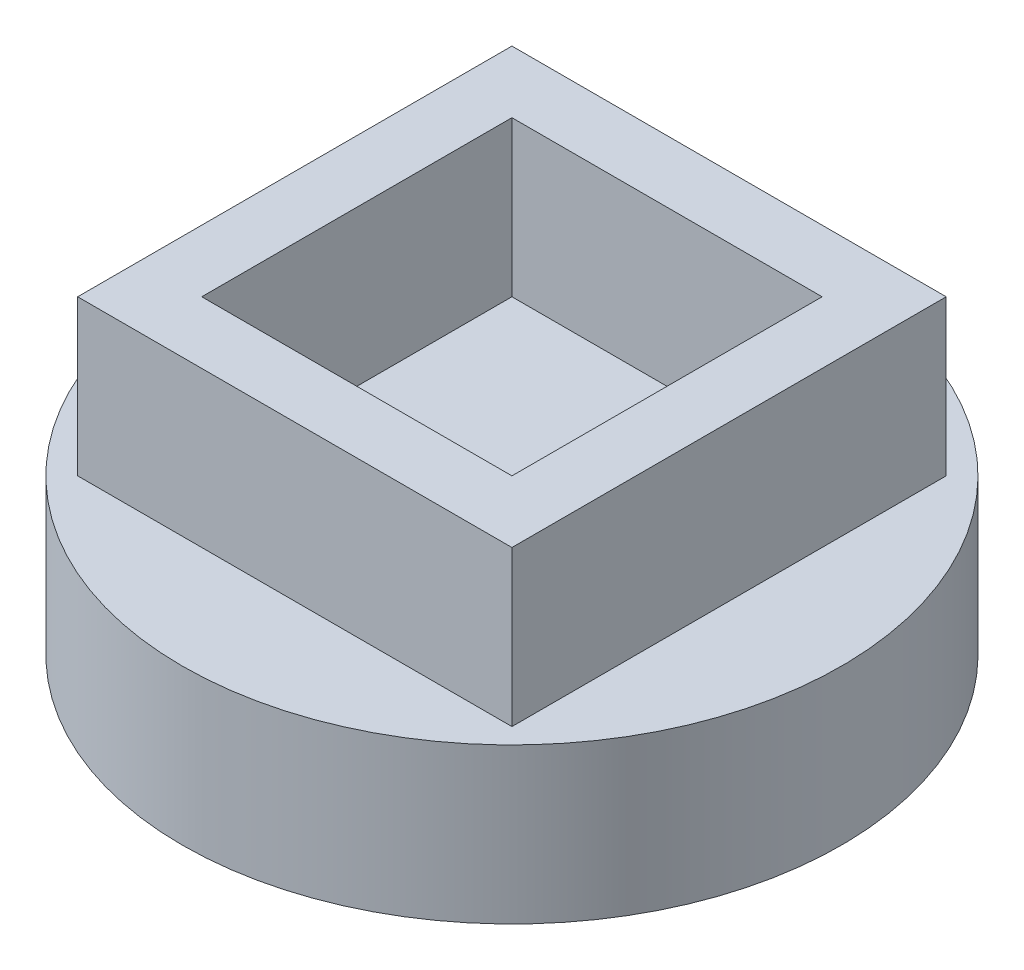
SolidWorks part; units mm, degrees
ref_plane "Plan de face" through (0, 0, 0) normal (0, 0, 1) x (1, 0, 0)
ref_plane "Plan de dessus" through (0, 0, 0) normal (0, 1, 0) x (1, 0, 0)
ref_plane "Plan de droite" through (0, 0, 0) normal (1, 0, 0) x (0, 0, -1)
sketch "Esquisse1" plane through (0, 0, 0) normal (0, 1, 0) x (1, 0, 0)
  circle A0 centre (0, 0) radius 4.25
  dimension "D1" = 8.5
extrude "Boss.-Extru.1" add sketch "Esquisse1" along normal blind 2
sketch "Esquisse2" plane through (0, 2, 0) normal (0, 1, 0) x (1, 0, 0)
  line L0 (-2.8, 2.8) -> (-2.8, -2.8)
  line L1 (-2, 2) -> (2, 2)
  line L2 (-2, 2) -> (-2, -2)
  line L3 (-2, -2) -> (2, -2)
  line L4 (2, 2) -> (2, -2)
  line L5 (-2, 2) -> (2, -2) construction
  line L6 (-2, -2) -> (2, 2) construction
  line L7 (-2.8, -2.8) -> (2.8, -2.8)
  line L8 (2.8, 2.8) -> (2.8, -2.8)
  line L9 (-2.8, 2.8) -> (2.8, 2.8)
  point P0 (0, 0)
  dimension "D1" = 4
  dimension "D2" = 0.8
extrude "Boss.-Extru.2" add sketch "Esquisse2" along normal blind 2
